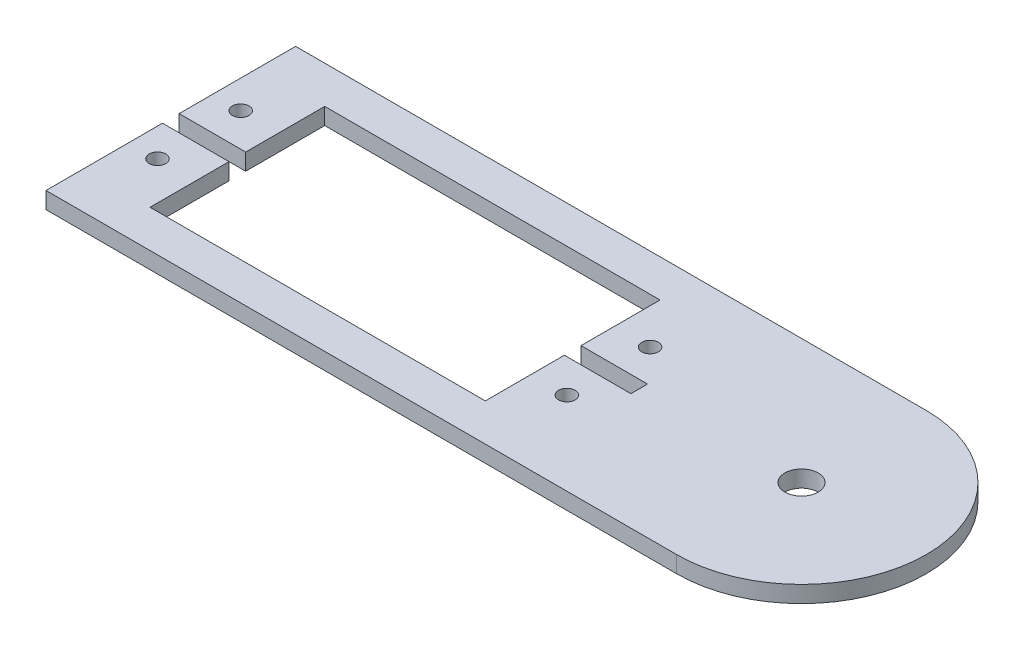
SolidWorks part; units mm, degrees
ref_plane "Спереди" through (0, 0, 0) normal (0, 0, 1) x (1, 0, 0)
ref_plane "Сверху" through (0, 0, 0) normal (0, 1, 0) x (1, 0, 0)
ref_plane "Справа" through (0, 0, 0) normal (1, 0, 0) x (0, 0, -1)
sketch "Эскиз1" plane through (0, 0, 0) normal (0, 1, 0) x (1, 0, 0)
  line L0 (3.4, 10) -> (3.4, 21) construction
  line L1 (0, 0) -> (93, 0) construction
  line L2 (0, 0) -> (0, 30) construction
  line L3 (0, 30) -> (93, 30) construction
  line L4 (93, 0) -> (93, 30) construction
  line L5 (8, 25.5) -> (48.3, 25.5)
  line L6 (8, 25.5) -> (8, 4.5) construction
  line L7 (8, 4.5) -> (48.3, 4.5)
  line L8 (48.3, 25.5) -> (48.3, 16)
  line L9 (2.4, 10) -> (2.4, 20) construction
  line L10 (3.4, 10) -> (53.6, 10) construction
  line L11 (3.4, 20) -> (53.6, 20) construction
  line L12 (3.4, 9) -> (52.6, 9) construction
  line L13 (52.6, 10) -> (52.6, 21) construction
  line L14 (53.6, 10) -> (53.6, 20) construction
  line L15 (0, 16) -> (8, 16)
  line L16 (0, 14) -> (8, 14)
  line L17 (56.3, 14) -> (56.3, 16)
  line L18 (48.3, 14) -> (48.3, 4.5)
  line L19 (48.3, 16) -> (56.3, 16)
  line L20 (48.3, 14) -> (56.3, 14)
  line L21 (8, 4.5) -> (8, 14)
  line L22 (8, 16) -> (8, 25.5)
  line L23 (0, 30) -> (0, 16)
  line L24 (0, 14) -> (0, 0)
  line L25 (0, 30) -> (75.8, 30)
  line L26 (0, 0) -> (75.8, 0)
  circle A0 centre (3.4, 10) radius 1
  circle A1 centre (3.4, 20) radius 1
  circle A2 centre (52.6, 10) radius 1
  circle A3 centre (52.6, 20) radius 1
  circle A4 centre (75.8, 15) radius 2
  arc A5 (75.8, 0) -> (75.8, 30) centre (75.8, 15) ccw
  point P9 (8, 15)
  point P10 (0, 15)
  point P38 (93, 15)
  dimension "D6" = 2
  dimension "D9" = 10
  dimension "D10" = 49.2
  dimension "D11" = 1
  dimension "D13" = 4
  dimension "D1" = 93
  dimension "D2" = 30
  dimension "D3" = 40.3
  dimension "D4" = 21
  dimension "D5" = 8
  dimension "D7" = 3.4
  dimension "D8" = 5
  dimension "D12" = 2
  dimension "D14" = 27.5
extrude "Бобышка-Вытянуть1" add sketch "Эскиз1" along normal blind 2
